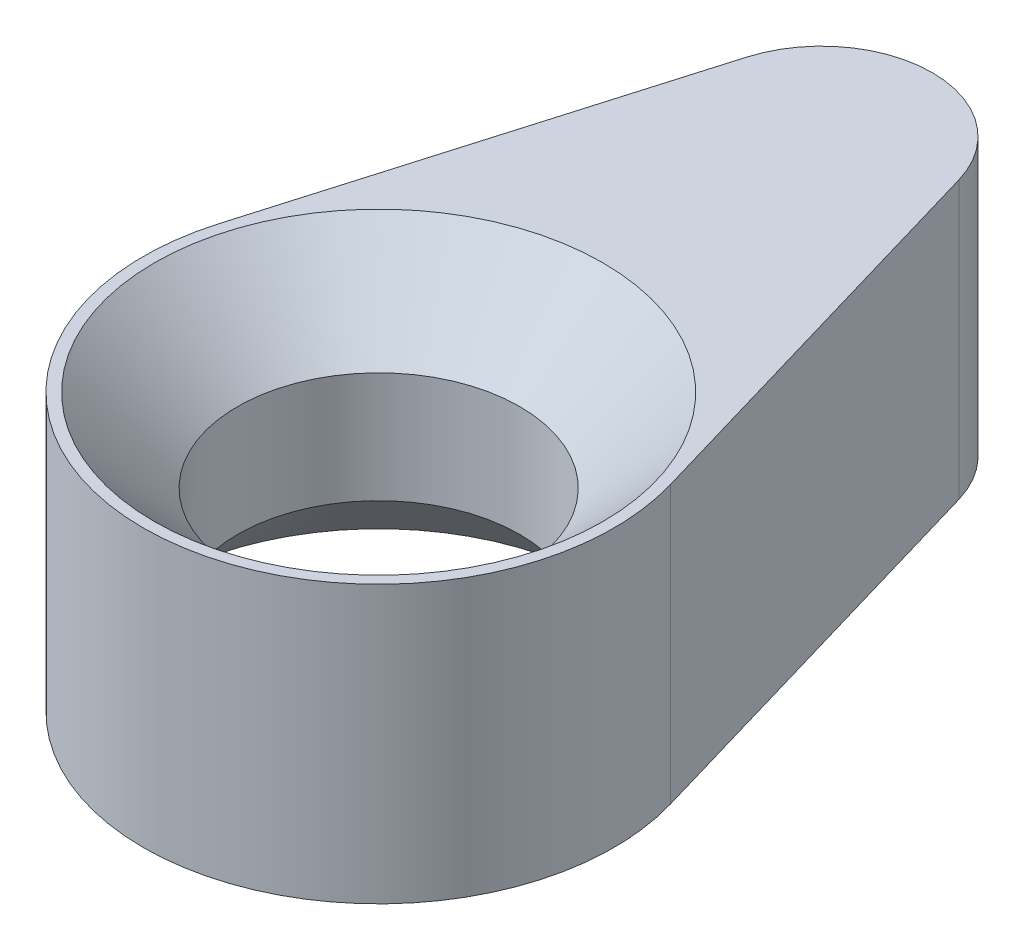
SolidWorks part; units mm, degrees
ref_plane "Front Plane" through (0, 0, 0) normal (0, 0, 1) x (1, 0, 0)
ref_plane "Top Plane" through (0, 0, 0) normal (0, 1, 0) x (1, 0, 0)
ref_plane "Right Plane" through (0, 0, 0) normal (1, 0, 0) x (0, 0, -1)
sketch "Sketch1" plane through (0, 0, 0) normal (0, 1, 0) x (1, 0, 0)
  line L0 (-10.3593, 3.0361) -> (-4.8749, 21.7488)
  line L1 (4.8749, 21.7488) -> (10.3593, 3.0361)
  circle A0 centre (0, 0) radius 6.477
  circle A1 centre (0, 0) radius 10.795
  arc A2 (-4.8749, 21.7488) -> (4.8749, 21.7488) centre (0, 20.32) cw
  dimension "D1" = 12.954
  dimension "D2" = 5.08
  dimension "D3" = 21.59
  dimension "D4" = 20.32
extrude "Boss-Extrude1" add sketch "Sketch1" along normal blind 12.7 contours A2 L0 A1 L1 | A1 A0
chamfer "Chamfer1" distance 3.81 angle 45 2 edges at (0, 12.7, 6.477) (0, 0, 6.477)
